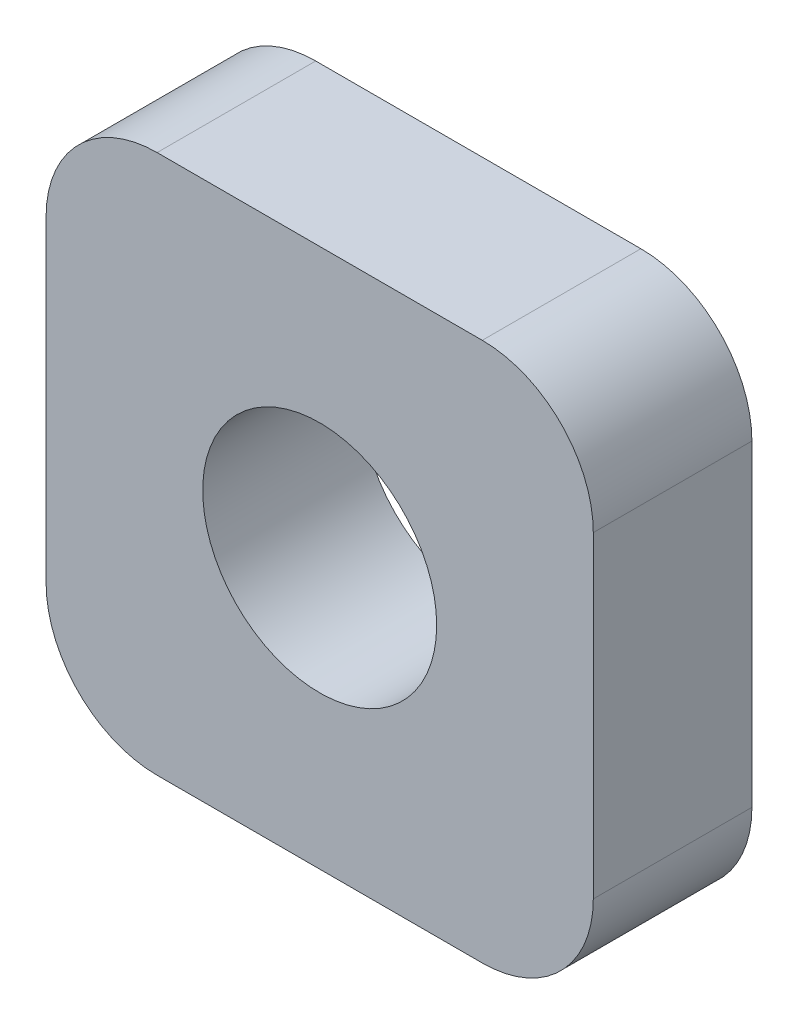
SolidWorks part; units mm, degrees
ref_plane "Front Plane" through (0, 0, 0) normal (0, 0, 1) x (1, 0, 0)
ref_plane "Top Plane" through (0, 0, 0) normal (0, 1, 0) x (1, 0, 0)
ref_plane "Right Plane" through (0, 0, 0) normal (1, 0, 0) x (0, 0, -1)
sketch "Sketch1" plane through (0, 0, 0) normal (0, 0, 1) x (1, 0, 0)
  line L0 (-3.45, 7) -> (-3.45, 3)
  line L1 (-2.05, 1.6) -> (2.05, 1.6)
  line L2 (3.45, 3) -> (3.45, 7)
  line L3 (2.05, 8.4) -> (-2.05, 8.4)
  line L4 (-5.05, 5) -> (5.05, 5) construction
  line L7 (0, 10) -> (0, 0) construction
  arc A0 (-3.45, 3) -> (-2.05, 1.6) centre (-2.05, 3) ccw
  arc A1 (2.05, 1.6) -> (3.45, 3) centre (2.05, 3) ccw
  arc A2 (3.45, 7) -> (2.05, 8.4) centre (2.05, 7) ccw
  arc A3 (-2.05, 8.4) -> (-3.45, 7) centre (-2.05, 7) ccw
  circle A4 centre (0, 5) radius 1.475
  dimension "D2" = 2.95
extrude "Boss-Extrude1" add sketch "Sketch1" along normal blind 2
